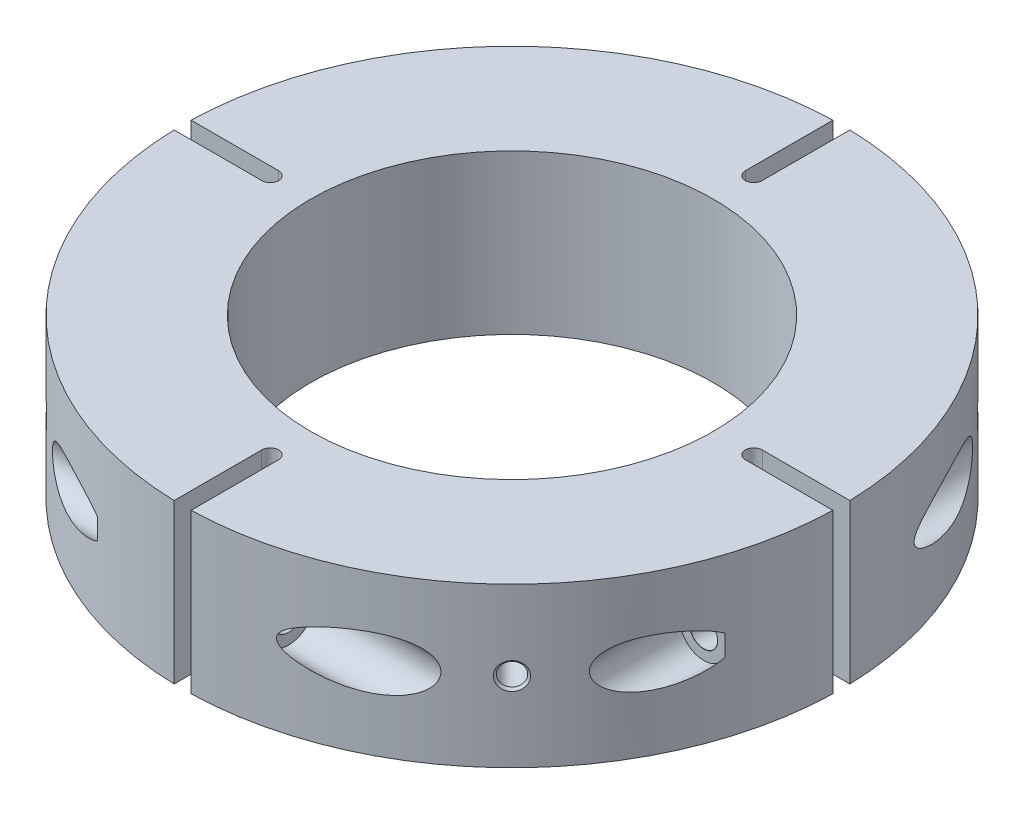
SolidWorks part; units mm, degrees
material "Delrin 2700 NC010, Düşük Viskozite Asetal Kopolimer (SS)"
ref_plane "Ön Düzlem" through (0, 0, 0) normal (0, 0, 1) x (1, 0, 0)
ref_plane "Üst Düzlem" through (0, 0, 0) normal (0, 1, 0) x (1, 0, 0)
ref_plane "Sağ Düzlem" through (0, 0, 0) normal (1, 0, 0) x (0, 0, -1)
sketch "Çizim1" plane through (0, 0, 0) normal (0, 1, 0) x (1, 0, 0)
  line L0 (-61.4792, 0) -> (61.4792, 0) construction
  line L1 (0, 61.4792) -> (0, -61.4792) construction
  line L3 (-1.6, 45.6794) -> (-1.6, 62.1794)
  line L4 (1.6, 45.6794) -> (1.6, 62.1794)
  line L6 (45.6794, -1.6) -> (62.1794, -1.6)
  line L7 (45.6794, 1.6) -> (62.1794, 1.6)
  line L8 (-1.6, -45.6794) -> (-1.6, -62.1794)
  line L9 (1.6, -45.6794) -> (1.6, -62.1794)
  line L10 (-45.6794, 1.6) -> (-62.1794, 1.6)
  line L11 (-45.6794, -1.6) -> (-62.1794, -1.6)
  circle A0 centre (0, 0) radius 38
  arc A1 (-1.6, 62.1794) -> (-62.1794, 1.6) centre (0, 0) ccw
  arc A2 (-1.6, 45.6794) -> (1.6, 45.6794) centre (0, 45.6368) ccw
  arc A3 (45.6794, 1.6) -> (45.6794, -1.6) centre (45.6368, 0) ccw
  arc A4 (1.6, -45.6794) -> (-1.6, -45.6794) centre (0, -45.6368) ccw
  arc A5 (-45.6794, -1.6) -> (-45.6794, 1.6) centre (-45.6368, 0) ccw
  arc A6 (62.1794, 1.6) -> (1.6, 62.1794) centre (0, 0) ccw
  arc A7 (1.6, -62.1794) -> (62.1794, -1.6) centre (0, 0) ccw
  arc A8 (-62.1794, -1.6) -> (-1.6, -62.1794) centre (0, 0) ccw
  point P7 (0, 0)
  point P10 (0, 0)
  point P32 (0, 0)
  dimension "D1" = 62.2
  dimension "D2" = 16.5
  dimension "D3" = 1.6
  dimension "D4" = 3.2
  dimension "D7" = 4
extrude "Yükseklik-Ekstrüzyon1" add sketch "Çizim1" along normal blind 30
ref_plane "Düzlem1" through (0, 0, 38) normal (0, 0, 1) x (1, 0, 0)
hole_wizard "M5 Altıgen Alyan Başlı Kör Vida İçin Havşa1" positions "Çizim2" profile "Çizim3" counterbore size "M5" standard "DIN"
sketch "Çizim2" plane through (0, 0, 38) normal (0, 0, 1) x (1, 0, 0)
  line L0 (-62.1794, 30) -> (-62.1794, 0) construction
  point P0 (-55.1794, 15.1565)
  dimension "D1" = 7
sketch "Çizim3" plane through (-55.1794, 15.1565, 38) normal (1, 0, 0) x (0, -1, 0)
  line L0 (0, 0) -> (0, 39.7425)
  line L1 (0, 39.7425) -> (2.9, 38)
  line L2 (2.9, 38) -> (2.9, 25)
  line L3 (2.9, 25) -> (5, 25)
  line L5 (5, 25) -> (5, 0.025)
  line L6 (5, 0.025) -> (5.025, 0)
  line L7 (5.025, 0) -> (0, 0)
  line L8 (-5, 0.025) -> (-5.025, 0) construction
  line L10 (0, 39.7425) -> (-2.9, 38) construction
  line L11 (0, -6.35) -> (0, 107.95) construction
  dimension "Hole Dia." = 5.8
  dimension "Hole Depth" = 38
  dimension "C'Bore Dia." = 10
  dimension "C'Bore Depth" = 25
  dimension "Near C'Sink Dia." = 10.05
  dimension "Near C'Sink Angle" = 90
  dimension "Drill Angle" = 118
sketch "Çizim31" plane through (0, 0, 38) normal (0, 0, 1) x (1, 0, 0)
  circle A0 centre (-55.1794, 15.1565) radius 4.5
extrude "Kes-Ekstrüzyon4" cut sketch "Çizim31" against normal blind 40 from offset 57 offset against normal yes
sketch "Çizim4" plane through (0, 0, -19) normal (0, 0, -1) x (-1, 0, 0)
  point P0 (55.1794, 15.1565)
hole_wizard "M5 Helisarmal için Zıvana matkabı3" positions "3B Çizim5" profile "Çizim6" hole size "M5x0.8" standard "DIN"
sketch3d "3B Çizim5"
  point P0 (-55.1794, 15.1565, -19)
sketch "Çizim6" plane through (-55.1794, 15.1565, -19) normal (1, 0, 0) x (0, 1, 0)
  line L0 (0, 0) -> (0, 19.5622)
  line L1 (0, 19.5622) -> (2.6, 18)
  line L2 (2.6, 18) -> (2.6, 0.025)
  line L3 (2.6, 0.025) -> (2.625, 0)
  line L5 (2.625, 0) -> (0, 0)
  line L6 (-2.6, 0.025) -> (-2.625, 0) construction
  line L10 (0, 19.5622) -> (-2.6, 18) construction
  line L11 (0, -6.35) -> (0, 107.95) construction
  dimension "Hole Dia." = 5.2
  dimension "Hole Depth" = 18
  dimension "Near C'Sink Dia." = 5.25
  dimension "Near C'Sink Angle" = 90
  dimension "Drill Angle" = 118
sketch "Çizim32" plane through (0, 30, 0) normal (0, 1, 0) x (1, 0, 0)
  line L0 (0, 0) -> (-43.982, -43.982) construction
  line L1 (0, 0) -> (-61.5, 0) construction
  line L2 (0, 0) -> (43.982, -43.982) construction
  arc A0 (-62.1794, -1.6) -> (-1.6, -62.1794) centre (0, 0) ccw construction
  arc A1 (1.6, -62.1794) -> (62.1794, -1.6) centre (0, 0) ccw construction
  dimension "D1" = 61.5
  dimension "D2" = 45
  dimension "D3" = 90
hole_wizard "M5x0.8 Helisarmal İçin Dişli Delik1" positions "3B Çizim7" profile "Çizim8" tap size "M5x0.8" standard "Helicoil® Metric"
sketch3d "3B Çizim7"
  line L0 (0, 30, 0) -> (-43.982, 30, 43.982) construction
  point P0 (-43.982, 15, 43.982)
  dimension "D1" = 15
sketch "Çizim8" plane through (-43.982, 15, 43.982) normal (0, 1, 0) x (0.7071, 0, 0.7071)
  line L0 (0, 0) -> (0, 13.2463)
  line L1 (0, 13.2463) -> (2.6, 12.3)
  line L2 (2.6, 12.3) -> (2.6, 0.4975)
  line L3 (2.6, 0.4975) -> (3.0975, 0)
  line L5 (3.0975, 0) -> (0, 0)
  line L6 (-2.6, 0.4975) -> (-3.0975, 0) construction
  line L10 (0, 13.2463) -> (-2.6, 12.3) construction
  line L11 (0, -6.35) -> (0, 107.95) construction
  dimension "Tap Drill Dia." = 5.2
  dimension "Tap Drill Depth" = 12.3
  dimension "Near C'Sink Dia." = 6.195
  dimension "Near C'Sink Angle" = 90
  dimension "Drill Angle" = 140
cosmetic thread "Delik Dişi1" parameters "D1"=5.8, "D2"=6.145
pattern_circular "Dairesel Kaplama1" count 4 every 90 about axis through (0, 0, 0) along (0, 1, 0) of "M5 Altıgen Alyan Başlı Kör Vida İçin Havşa1", "Kes-Ekstrüzyon4", "M5 Helisarmal için Zıvana matkabı3"
pattern_circular "Dairesel Kaplama2" count 3 every 90 about axis through (0, 30, 0) along (0, -1, 0) of "M5x0.8 Helisarmal İçin Dişli Delik1"
cosmetic thread "Delik Dişi2" parameters "D1"=5.8, "D2"=6.145
cosmetic thread "Delik Dişi3" parameters "D1"=5.8, "D2"=6.145
hole_wizard "M4x0.7 Helisarmal İçin Dişli Delik1" positions "3B Çizim9" profile "Çizim10" tap size "M4x0.7" standard "Helicoil® Metric"
sketch3d "3B Çizim9"
  point P0 (43.982, 15, 43.982)
  dimension "D1" = 15
sketch "Çizim10" plane through (43.982, 15, 43.982) normal (0, 1, 0) x (0.7071, 0, -0.7071)
  line L0 (0, 0) -> (0, 10.9643)
  line L1 (0, 10.9643) -> (2.1, 10.2)
  line L2 (2.1, 10.2) -> (2.1, 0.4285)
  line L3 (2.1, 0.4285) -> (2.5285, 0)
  line L5 (2.5285, 0) -> (0, 0)
  line L6 (-2.1, 0.4285) -> (-2.5285, 0) construction
  line L10 (0, 10.9643) -> (-2.1, 10.2) construction
  line L11 (0, -6.35) -> (0, 107.95) construction
  dimension "Tap Drill Dia." = 4.2
  dimension "Tap Drill Depth" = 10.2
  dimension "Near C'Sink Dia." = 5.057
  dimension "Near C'Sink Angle" = 90
  dimension "Drill Angle" = 140
cosmetic thread "Delik Dişi4" parameters "D1"=4.7, "D2"=5.007
